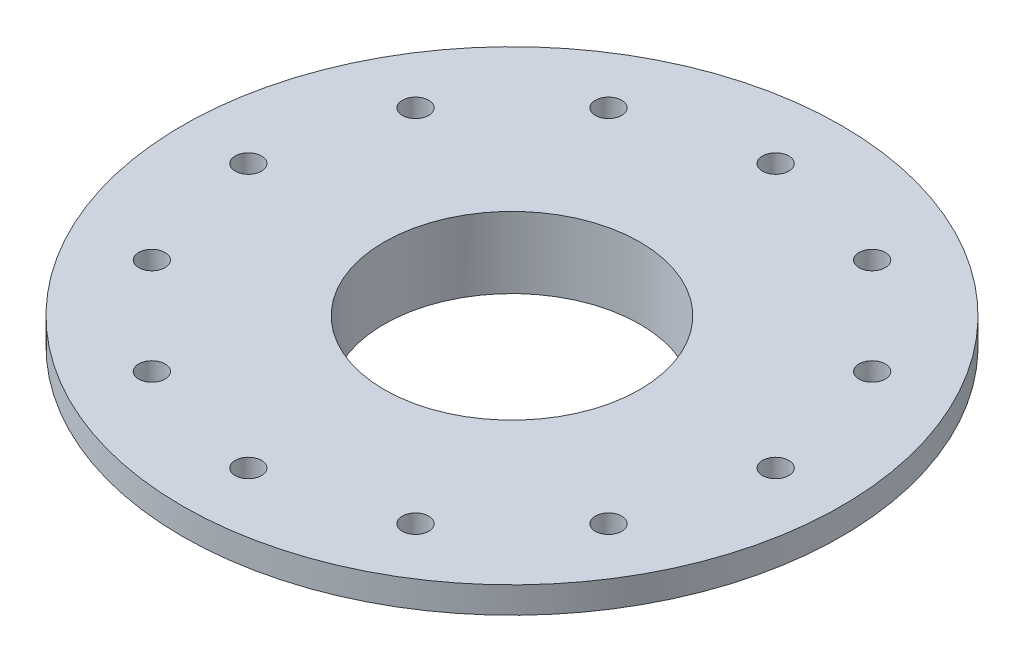
SolidWorks part; units mm, degrees
ref_plane "Front Plane" through (0, 0, 0) normal (0, 0, 1) x (1, 0, 0)
ref_plane "Top Plane" through (0, 0, 0) normal (0, 1, 0) x (1, 0, 0)
ref_plane "Right Plane" through (0, 0, 0) normal (1, 0, 0) x (0, 0, -1)
sketch "Sketch2" plane through (0, 0, 0) normal (0, 1, 0) x (1, 0, 0)
  circle A0 centre (0, 0) radius 125
extrude "Boss-Extrude1" add sketch "Sketch2" along normal blind 10
sketch "Sketch3" plane through (0, 10, 0) normal (0, 1, 0) x (1, 0, 0)
  line L0 (0, 0) -> (144.9589, 0) construction
  circle A0 centre (0, 0) radius 100 construction
  circle A1 centre (100, 0) radius 5
  circle A2 centre (86.6025, -50) radius 5
  circle A3 centre (50, -86.6025) radius 5
  circle A4 centre (0, -100) radius 5
  circle A5 centre (-50, -86.6025) radius 5
  circle A6 centre (-86.6025, -50) radius 5
  circle A7 centre (-100, 0) radius 5
  circle A8 centre (-86.6025, 50) radius 5
  circle A9 centre (-50, 86.6025) radius 5
  circle A10 centre (0, 100) radius 5
  circle A11 centre (50, 86.6025) radius 5
  circle A12 centre (86.6025, 50) radius 5
  point P30 (0, 0)
  dimension "D1" = 12
  dimension "D2" = 200
extrude "Cut-Extrude1" cut sketch "Sketch3" against normal blind 10
sketch "Sketch4" plane through (0, 0, 0) normal (0, -1, 0) x (1, 0, 0)
  circle A0 centre (0, 0) radius 107.5
extrude "Boss-Extrude2" add sketch "Sketch4" along normal blind 17
chamfer "Chamfer1" distance 10 angle 45 1 edges at (0, -17, -107.5)
sketch "Sketch5" plane through (0, -17, 0) normal (0, -1, 0) x (1, 0, 0)
  circle A0 centre (0, 0) radius 48.5
extrude "Cut-Extrude2" cut sketch "Sketch5" against normal blind 57
